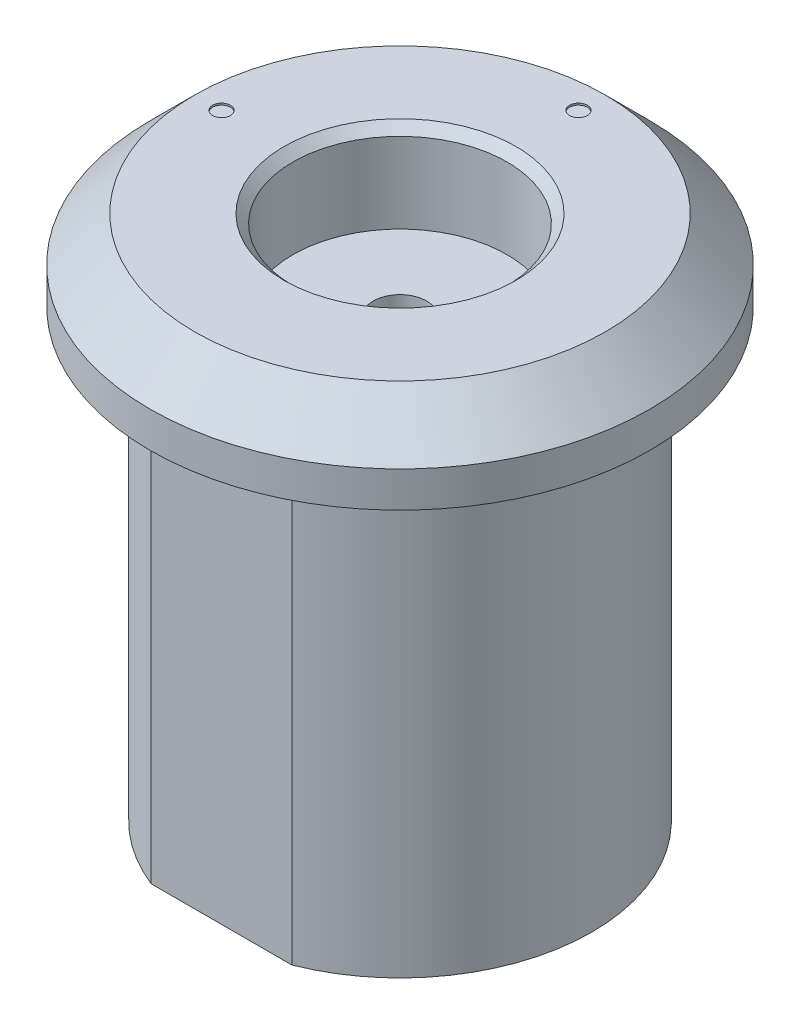
SolidWorks part; units mm, degrees
ref_plane "前视基准面" through (0, 0, 0) normal (0, 0, 1) x (1, 0, 0)
ref_plane "上视基准面" through (0, 0, 0) normal (0, 1, 0) x (1, 0, 0)
ref_plane "右视基准面" through (0, 0, 0) normal (1, 0, 0) x (0, 0, -1)
sketch "草图1" plane through (0, 0, 0) normal (0, 1, 0) x (1, 0, 0)
  circle A0 centre (0, 0) radius 14
  dimension "D1" = 28
extrude "凸台-拉伸1" add sketch "草图1" along normal blind 4.5
sketch "草图8" plane through (0, 4.5, 0) normal (0, 1, 0) x (1, 0, 0)
  circle A0 centre (-10, 0) radius 0.5
  circle A1 centre (0, 10) radius 0.5
  circle A2 centre (0, 0) radius 10 construction
  dimension "D2" = 1
  dimension "D3" = 1
  dimension "D1" = 20
extrude "开关示意点" cut sketch "草图8" against normal blind 0.1
chamfer "倒角1" distance 2.5 angle 45 1 edges at (0, 4.5, 14)
sketch "草图2" plane through (0, 0, 0) normal (0, -1, 0) x (1, 0, 0)
  circle A0 centre (0, 0) radius 10.75
  dimension "D1" = 21.5
extrude "凸台-拉伸2" add sketch "草图2" along normal blind 25
sketch "草图3" plane through (0, -25, 0) normal (0, -1, 0) x (1, 0, 0)
  line L0 (-3.9449, -10) -> (3.9449, -10)
  line L1 (-3.9449, 10) -> (3.9449, 10)
  circle A0 centre (0, 0) radius 10.75 construction
  circle A1 centre (0, 0) radius 10.75 construction
  arc A2 (-3.9449, -10) -> (3.9449, -10) centre (0, 0) ccw
  arc A3 (-3.9449, 10) -> (3.9449, 10) centre (0, 0) cw
  dimension "D1" = 20
extrude "切除-拉伸1" cut sketch "草图3" against normal up to surface (25 mm away) up to face at (0, 0, 10.75)
sketch "草图4" plane through (0, 4.5, 0) normal (0, 1, 0) x (1, 0, 0)
  circle A0 centre (0, 0) radius 6
extrude "切除-拉伸2" cut sketch "草图4" against normal blind 5
chamfer "倒角2" distance 0.5 angle 45 1 edges at (0, 4.5, 6)
sketch "草图6" plane through (0, -25, 0) normal (0, -1, 0) x (1, 0, 0)
  circle A0 centre (0, 0) radius 8
  dimension "D1" = 16
extrude "切除-拉伸3" cut sketch "草图6" against normal blind 20
sketch "草图7" plane through (0, -0.5, 0) normal (0, 1, 0) x (1, 0, 0)
  line L0 (0.5, -2) -> (0.5, -1.4142)
  line L1 (0.5, -2) -> (-0.5, -2)
  line L3 (-0.5, -2) -> (-0.5, -1.4142)
  line L4 (0, 0) -> (0, -5.2469) construction
  arc A0 (0.5, -1.4142) -> (-0.5, -1.4142) centre (0, 0) ccw
  dimension "D1" = 3
  dimension "D2" = 1
  dimension "D3" = 2
extrude "切除-拉伸4" cut sketch "草图7" against normal through all
